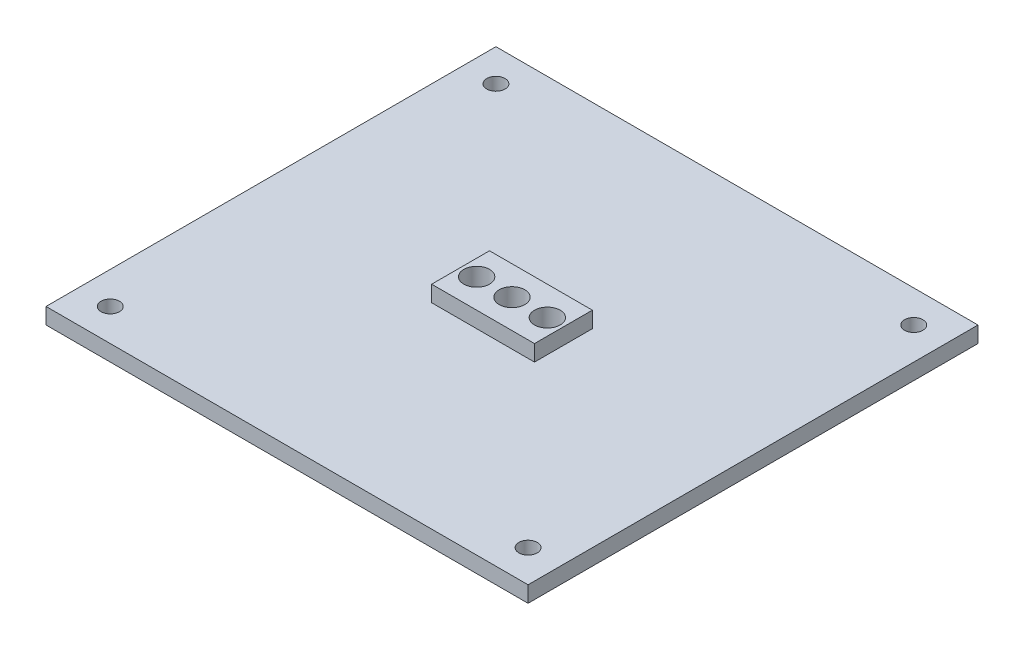
SolidWorks part; units mm, degrees
ref_plane "Front Plane" through (0, 0, 0) normal (0, 0, 1) x (1, 0, 0)
ref_plane "Top Plane" through (0, 0, 0) normal (0, 1, 0) x (1, 0, 0)
ref_plane "Right Plane" through (0, 0, 0) normal (1, 0, 0) x (0, 0, -1)
sketch "Sketch1" plane through (0, 0, 0) normal (0, 1, 0) x (1, 0, 0)
  line L0 (-75.546, 118.4572) -> (-75.546, -21.5428)
  line L1 (-65.546, 108.4572) -> (64.454, 108.4572) construction
  line L2 (-65.546, 108.4572) -> (-65.546, -11.5428) construction
  line L3 (-65.546, -11.5428) -> (64.454, -11.5428) construction
  line L4 (64.454, 108.4572) -> (64.454, -11.5428) construction
  line L5 (-75.546, -21.5428) -> (74.454, -21.5428)
  line L6 (74.454, 118.4572) -> (74.454, -21.5428)
  line L7 (-75.546, 118.4572) -> (74.454, 118.4572)
  line L8 (-65.546, 48.4572) -> (64.454, 48.4572) construction
  circle A0 centre (-65.546, 108.4572) radius 2.85
  circle A1 centre (64.454, 108.4572) radius 2.85
  circle A2 centre (64.454, -11.5428) radius 2.85
  circle A3 centre (-65.546, -11.5428) radius 2.85
  circle A4 centre (-11.546, 48.4572) radius 4
  circle A5 centre (-0.546, 48.4572) radius 4
  circle A6 centre (10.454, 48.4572) radius 4
  dimension "D4" = 5.7
  dimension "D5" = 5.7
  dimension "D6" = 5.7
  dimension "D7" = 5.7
  dimension "D8" = 8
  dimension "D9" = 8
  dimension "D10" = 8
  dimension "D2" = 150
  dimension "D3" = 140
  dimension "D11" = 11
  dimension "D12" = 11
  dimension "D1" = 10
extrude "Boss-Extrude1" add sketch "Sketch1" along normal blind 5
sketch "Sketch2" plane through (0, 5, 0) normal (0, 1, 0) x (1, 0, 0)
  line L0 (-11.546, 44.4572) -> (10.454, 44.4572)
  line L5 (10.454, 44.4572) -> (10.454, 52.4572) construction
  line L6 (10.454, 52.4572) -> (-11.546, 52.4572)
  line L7 (-11.546, 52.4572) -> (-11.546, 44.4572) construction
  line L8 (-16.546, 57.4572) -> (-16.546, 39.4572)
  line L9 (-16.546, 39.4572) -> (15.454, 39.4572)
  line L10 (15.454, 39.4572) -> (15.454, 57.4572)
  line L11 (15.454, 57.4572) -> (-16.546, 57.4572)
  circle A0 centre (-0.546, 48.4572) radius 4 construction
  circle A1 centre (10.454, 48.4572) radius 4 construction
  circle A2 centre (-11.546, 48.4572) radius 4 construction
  circle A3 centre (-0.546, 48.4572) radius 4
  circle A4 centre (10.454, 48.4572) radius 4
  circle A5 centre (-11.546, 48.4572) radius 4
  circle M12 centre (-0.546, 48.4572) radius 4
  circle M16 centre (10.454, 48.4572) radius 4
  circle M17 centre (-11.546, 48.4572) radius 4
  dimension "D1" = 5
  dimension "D2" = 18
extrude "Boss-Extrude2" add sketch "Sketch2" along normal blind 5 contours L10 L11 L8 L9 L6 L0 M16 M17 | L6 L0 M12 M17 | L6 L0 M16 M12 | A3 | A5 | A4
equation "\"D4@Sketch1\"=5.7"
equation "\"D5@Sketch1\"=\"D4@Sketch1\""
equation "\"D6@Sketch1\"=\"D4@Sketch1\""
equation "\"D7@Sketch1\"=\"D4@Sketch1\""
equation "\"D8@Sketch1\"=8"
equation "\"D9@Sketch1\"=\"D8@Sketch1\""
equation "\"D10@Sketch1\"=\"D8@Sketch1\""
